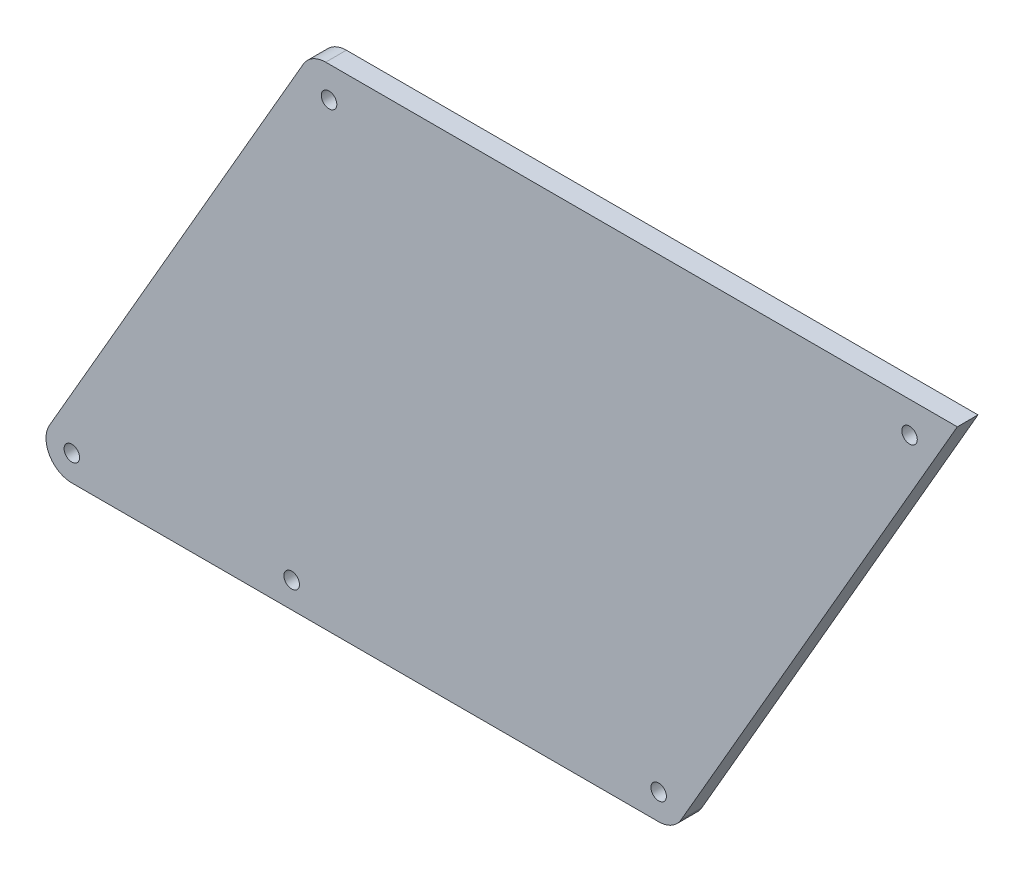
SolidWorks part; units mm, degrees
material "Pin"
ref_plane "Plan de face" through (0, 0, 0) normal (0, 0, 1) x (1, 0, 0)
ref_plane "Plan de dessus" through (0, 0, 0) normal (0, 1, 0) x (1, 0, 0)
ref_plane "Plan de droite" through (0, 0, 0) normal (1, 0, 0) x (0, 0, -1)
sketch "Esquisse1" plane through (0, 0, 0) normal (0, 0, 1) x (1, 0, 0)
  line L0 (5.7735, 0) -> (250, 0)
  line L1 (-2.8868, -5) -> (-101.0363, -175)
  line L2 (250, 0) -> (143.1902, -185)
  line L3 (-92.376, -190) -> (134.5299, -190)
  arc A0 (-2.8868, -5) -> (5.7735, 0) centre (5.7735, -10) cw
  arc A1 (143.1902, -185) -> (134.5299, -190) centre (134.5299, -180) cw
  arc A2 (-101.0363, -175) -> (-92.376, -190) centre (-92.376, -180) ccw
  point P7 (0, 0)
  dimension "D4" = 10
  dimension "D1" = 60
  dimension "D2" = 190
  dimension "D3" = 250
extrude "Boss.-Extru.1" add sketch "Esquisse1" along normal blind 8
extrude "Enlèv. mat.-Extru.1" cut sketch "Esquisse2" against normal through all
sketch "Esquisse2" plane through (-1216.4102, -630, 8) normal (0, 0, 1) x (1, 0, 0)
  line L1 (1447.935, 618) -> (1350.9401, 450) construction
  line L3 (1223.482, 618) -> (1209.482, 618) construction
  circle A2 centre (1124.0341, 450) radius 3
  circle A3 centre (1209.0341, 450) radius 3
  circle A4 centre (1223.482, 618) radius 3
  circle A5 centre (1447.935, 618) radius 3
  circle A6 centre (1350.9401, 450) radius 3
  point P16 (0, 0)
  point P23 (0, 0)
  point P25 (0, 0)
  point P27 (0, 0)
  point P28 (0, 0)
  point P31 (0, 0)
  point P32 (0, 0)
  point P33 (0, 0)
  point P34 (0, 0)
